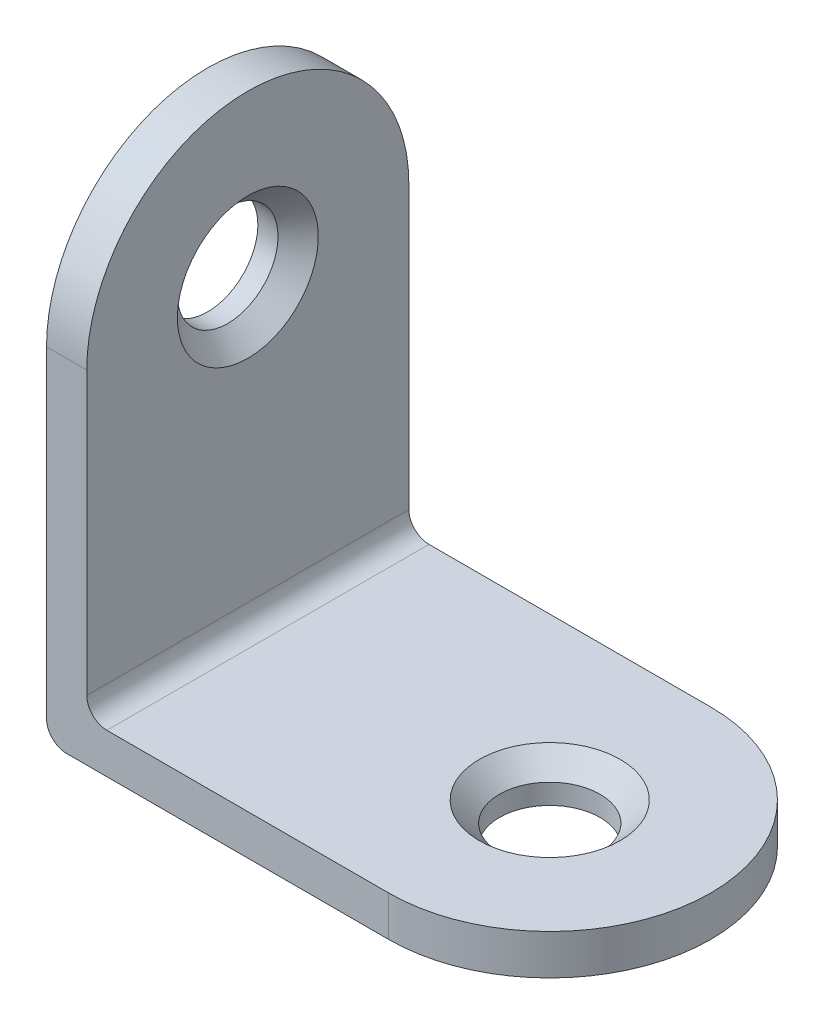
SolidWorks part; units mm, degrees
ref_plane "前视基准面" through (0, 0, 0) normal (0, 0, 1) x (1, 0, 0)
ref_plane "上视基准面" through (0, 0, 0) normal (0, 1, 0) x (1, 0, 0)
ref_plane "右视基准面" through (0, 0, 0) normal (1, 0, 0) x (0, 0, -1)
sketch "草图1" plane through (0, 0, 0) normal (0, 0, 1) x (1, 0, 0)
  line L0 (0, 0) -> (0, 23)
  line L1 (0, 23) -> (-2, 23)
  line L2 (-2, 23) -> (-2, -2)
  line L3 (-2, -2) -> (23, -2)
  line L4 (23, -2) -> (23, 0)
  line L5 (23, 0) -> (0, 0)
  dimension "D1" = 25
  dimension "D2" = 25
  dimension "D3" = 2
  dimension "D4" = 2
extrude "凸台-拉伸1" add sketch "草图1" along normal blind 16
sketch "草图2" plane through (0, 0, 0) normal (1, 0, 0) x (0, 0, -1)
  line L0 (-16, 23) -> (0, 23) construction
  line L1 (0, 0) -> (0, 23) construction
  line L6 (0, 0) -> (0, 23)
  line L7 (0, 23) -> (-16, 23)
  line L8 (-16, 23) -> (-16, 0)
  line L9 (-16, 0) -> (0, 0)
  line L10 (0, 15) -> (0, 23)
  line L11 (0, 23) -> (-16, 23)
  line L12 (-16, 23) -> (-16, 15)
  line L13 (-16, 0) -> (0, 0)
  arc A0 (0, 15) -> (-16, 15) centre (-8, 15) ccw
  line M5 (0, 0) -> (0, 23)
  line M6 (0, 23) -> (-16, 23)
  line M7 (-16, 23) -> (-16, 0)
  dimension "D1" = 16
  dimension "D2" = 0
extrude "切除-拉伸1" cut sketch "草图2" against normal blind 16 and the other way through all contours A0 L11 M7 | A0 M5 M6
sketch "草图3" plane through (0, -2, 0) normal (0, -1, 0) x (1, 0, 0)
  line L0 (23, 16) -> (23, 0) construction
  line L1 (-2, 16) -> (23, 16) construction
  line L6 (-2, 0) -> (23, 0)
  line L7 (23, 0) -> (23, 16)
  line L8 (23, 16) -> (-2, 16)
  line L9 (-2, 16) -> (-2, 0)
  line L10 (15, 0) -> (23, 0)
  line L11 (23, 0) -> (23, 16)
  line L12 (23, 16) -> (15, 16)
  line L13 (-2, 16) -> (-2, 0)
  arc A0 (15, 0) -> (15, 16) centre (15, 8) ccw
  line M5 (-2, 0) -> (23, 0)
  line M6 (23, 0) -> (23, 16)
  line M7 (23, 16) -> (-2, 16)
  dimension "D1" = 16
  dimension "D2" = 0
extrude "切除-拉伸2" cut sketch "草图3" against normal blind 16 and the other way through all contours A0 M5 M6 | A0 L11 M7
sketch "草图4" plane through (0, 0, 0) normal (0, 1, 0) x (1, 0, 0)
  circle A0 centre (15, -8) radius 2.5
  dimension "D1" = 5
extrude "切除-拉伸3" cut sketch "草图4" against normal blind 16
sketch "草图5" plane through (0, 0, 0) normal (1, 0, 0) x (0, 0, -1)
  circle A0 centre (-8, 15) radius 2.5
  dimension "D1" = 5
extrude "切除-拉伸4" cut sketch "草图5" against normal blind 16
fillet "圆角1" radius 1 1 edges at (0, 0, 8)
fillet "圆角2" radius 1 1 edges at (-2, -2, 8)
chamfer "倒角1" distance 1 angle 45 1 edges at (0, 15, 5.5)
chamfer "倒角2" distance 1 angle 45 1 edges at (12.5, 0, 8)
